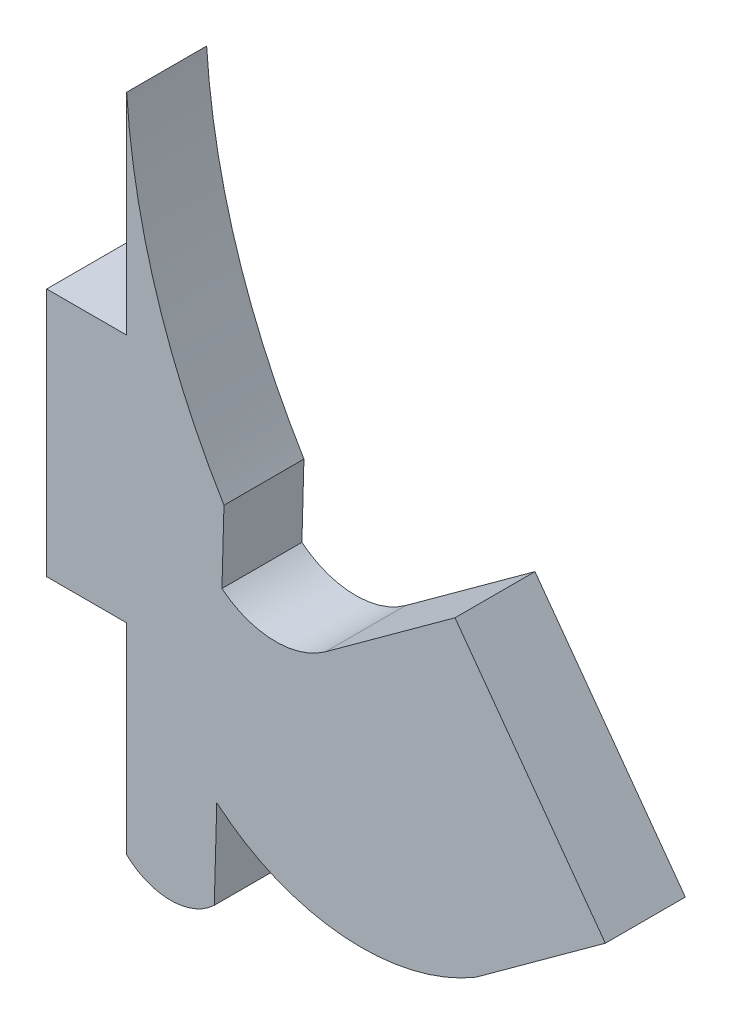
SolidWorks part; units mm, degrees
ref_plane "Front Plane" through (0, 0, 0) normal (0, 0, 1) x (1, 0, 0)
ref_plane "Top Plane" through (0, 0, 0) normal (0, 1, 0) x (1, 0, 0)
ref_plane "Right Plane" through (0, 0, 0) normal (1, 0, 0) x (0, 0, -1)
sketch "Sketch1" plane through (0, 0, 0) normal (0, 0, 1) x (1, 0, 0)
  line L0 (1.524, 26.9677) -> (0, 26.9677)
  line L1 (0, 26.9677) -> (0, 22.2179)
  line L2 (0, 22.2179) -> (1.524, 22.2179)
  line L3 (1.524, 22.2179) -> (1.524, 18.3913)
  line L4 (1.524, 26.9677) -> (1.524, 30.9774)
  line L5 (3.1937, 18.3913) -> (3.2411, 20.1101)
  line L6 (3.3399, 23.6931) -> (3.3784, 25.0875)
  line L7 (8.1815, 19.6991) -> (10.6465, 21.4918)
  line L9 (5.3165, 23.6386) -> (7.7816, 25.4313)
  line L10 (7.7816, 25.4313) -> (10.6465, 21.4918)
  arc A0 (1.524, 30.9774) -> (3.3784, 25.0875) centre (14.4741, 31.8177) ccw
  arc A1 (1.524, 18.3913) -> (3.1937, 18.3913) centre (2.3589, 19.2679) ccw
  arc A2 (3.2411, 20.1101) -> (8.1815, 19.6991) centre (5.9982, 23.3531) ccw
  arc A3 (3.3399, 23.6931) -> (5.3165, 23.6386) centre (4.3636, 24.9489) ccw
extrude "Boss-Extrude1" add sketch "Sketch1" along normal blind 1.524
